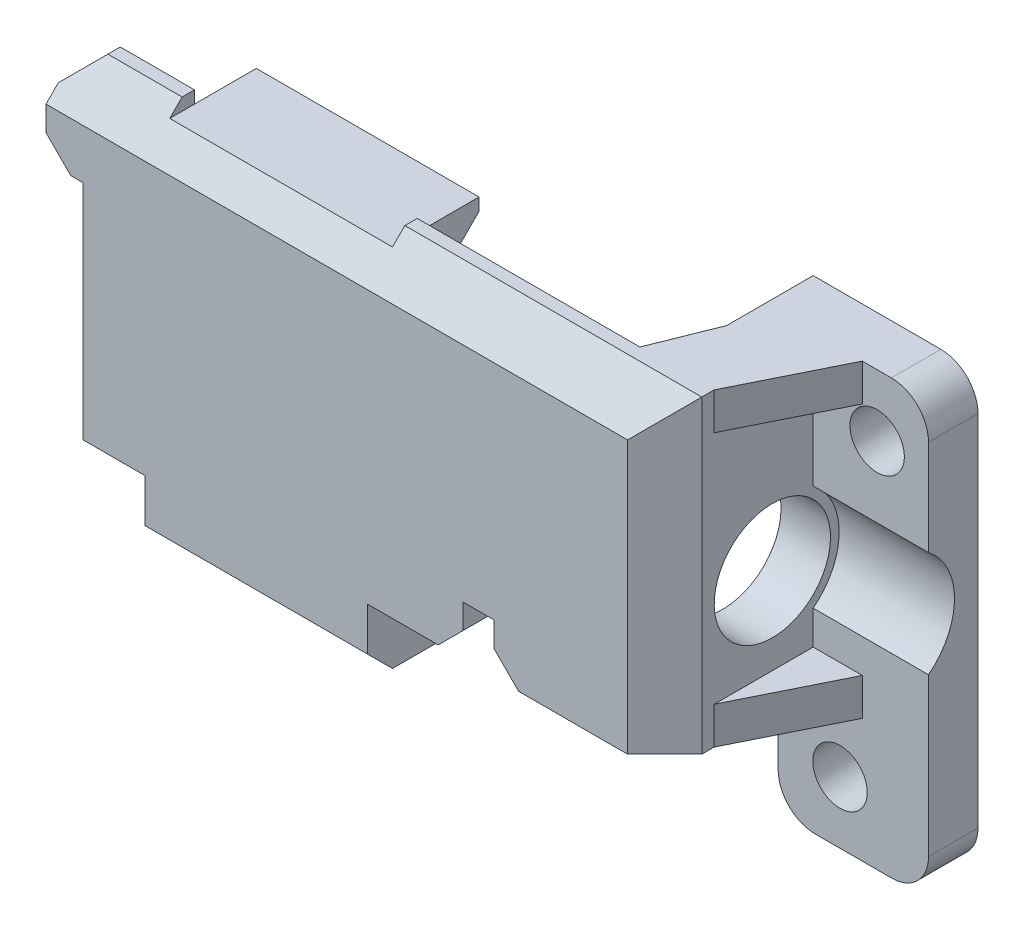
SolidWorks part; units mm, degrees
material "PEI"
ref_plane "前视基准面" through (0, 0, 0) normal (0, 0, 1) x (1, 0, 0)
ref_plane "上视基准面" through (0, 0, 0) normal (0, 1, 0) x (1, 0, 0)
ref_plane "右视基准面" through (0, 0, 0) normal (1, 0, 0) x (0, 0, -1)
other "Configuration Table"
sketch "草图1" plane through (0, 0, 0) normal (0, 0, 1) x (1, 0, 0)
  line L1 (0, 0) -> (9.32, 0)
  line L2 (0, 0) -> (0, 35)
  line L3 (0, 35) -> (9.32, 35)
  line L4 (9.32, 0) -> (9.32, 35)
  line L5 (0, 0) -> (-2.83, 0)
  line L6 (0, 0) -> (0, 10)
  line L7 (0, 10) -> (-2.83, 10)
  line L8 (-2.83, 0) -> (-2.83, 10)
  circle A0 centre (2.17, 5) radius 2.2
  circle A1 centre (5.17, 30) radius 2.2
  dimension "D1" = 4.4
  dimension "D2" = 3
  dimension "D3" = 25
  dimension "D4" = 5
  dimension "D5" = 4.15
  dimension "D6" = 5.17
  dimension "D7" = 5
  dimension "D8" = 5
  dimension "D9" = 10
extrude "凸台-拉伸2" add sketch "草图1" along normal blind 4 contours A0 L2 L1 L4 L3 A1 | A0 L2 L7 L8 L5
sketch "草图2" plane through (0, 0, 0) normal (0, 0, -1) x (-1, 0, 0)
  line L0 (0, 10) -> (2.83, 10) construction
  line L1 (0, 35) -> (4, 35)
  line L2 (0, 35) -> (0, 10)
  line L3 (0, 10) -> (4, 10)
  line L4 (4, 35) -> (4, 10)
  dimension "D2" = 4
extrude "凸台-拉伸3" add sketch "草图2" against normal blind 16
sketch "草图3" plane through (0, 0, 0) normal (1, 0, 0) x (0, 0, -1)
  line L0 (-16, 35) -> (-4, 35) construction
  line L1 (-16, 35) -> (-12, 35)
  line L2 (-16, 35) -> (-16, 10)
  line L3 (-16, 10) -> (-12, 10)
  line L4 (-12, 35) -> (-12, 10)
  line L5 (-16, 35) -> (-16, 10) construction
  line L6 (-16, 10) -> (-4, 10) construction
  dimension "D1" = 4
extrude "凸台-拉伸4" add sketch "草图3" against normal blind 50
sketch "草图4" plane through (0, 0, 12) normal (0, 0, -1) x (-1, 0, 0)
  line L0 (50, 10) -> (4, 10) construction
  line L1 (24, 10) -> (42, 10)
  line L2 (24, 10) -> (24, 3.5)
  line L3 (24, 3.5) -> (42, 3.5)
  line L4 (42, 10) -> (42, 3.5)
  line L5 (4, 35) -> (4, 10) construction
  line L6 (50, 10) -> (50, 35) construction
  dimension "D1" = 20
  dimension "D2" = 8
  dimension "D3" = 6.5
extrude "凸台-拉伸5" add sketch "草图4" against normal up to surface (4 mm away) up to face at (-25, 22.5, 16)
sketch "草图5" plane through (0, 0, 12) normal (0, 0, -1) x (-1, 0, 0)
  line L0 (42, 3.5) -> (42, 10) construction
  line L1 (24, 3.5) -> (42, 3.5)
  line L2 (24, 3.5) -> (24, 7.5)
  line L3 (24, 7.5) -> (42, 7.5)
  line L4 (42, 3.5) -> (42, 7.5)
  line L5 (50, 35) -> (4, 35) construction
  line L6 (24, 35) -> (42, 35)
  line L7 (24, 35) -> (24, 31)
  line L8 (24, 31) -> (42, 31)
  line L9 (42, 35) -> (42, 31)
  dimension "D1" = 4
  dimension "D2" = 18
  dimension "D3" = 4
extrude "凸台-拉伸6" add sketch "草图5" along normal blind 5
sketch "草图6" plane through (0, 0, 12) normal (0, 0, -1) x (-1, 0, 0)
  line L0 (24, 10) -> (4, 10) construction
  line L1 (13.8, 10) -> (16.3, 10)
  line L2 (13.8, 10) -> (13.8, 14)
  line L3 (13.8, 14) -> (16.3, 14)
  line L4 (16.3, 10) -> (16.3, 14)
  line L5 (24, 10) -> (24, 7.5) construction
  line L7 (50, 10) -> (47, 10)
  line L8 (50, 10) -> (50, 28)
  line L9 (50, 28) -> (47, 28)
  line L10 (47, 10) -> (47, 28)
  dimension "D1" = 2.5
  dimension "D2" = 7.7
  dimension "D3" = 4
  dimension "D4" = 3
  dimension "D5" = 18
extrude "切除-拉伸1" cut sketch "草图6" against normal up to surface (4 mm away) up to face at (-29, 14.625, 16)
sketch "草图7" plane through (0, 0, 0) normal (1, 0, 0) x (0, 0, -1)
  line L0 (-12, 35) -> (-12, 10) construction
  line L1 (-16, 10) -> (-4, 10) construction
  circle A0 centre (-7.3, 20) radius 4.7
  dimension "D1" = 9.4
  dimension "D2" = 10
extrude "切除-拉伸2" cut sketch "草图7" against normal through all both and the other way through all
sketch "草图8" plane through (0, 0, 0) normal (1, 0, 0) x (0, 0, -1)
  arc A0 (-4, 23.3466) -> (-4, 16.6534) centre (-7.3, 20) ccw construction
  arc A1 (-4, 23.3466) -> (-4, 16.6534) centre (-7.3, 20) ccw
  circle A2 centre (-7.3, 20) radius 5.4
  arc M1 (-4, 16.6534) -> (-4, 23.3466) centre (-7.3, 20) cw
  line M2 (-4, 23.3466) -> (-4, 35)
  line M6 (-4, 10) -> (-4, 16.6534)
  dimension "D1" = 10.8
extrude "切除-拉伸3" cut sketch "草图8" along normal through all contours A2 M6 M2 M1
sketch "草图9" plane through (0, 10, 0) normal (0, -1, 0) x (1, 0, 0)
  line L0 (3.97, 4) -> (-0.03, 4)
  line L1 (-2.83, 4) -> (9.32, 4) construction
  line L2 (-0.03, 4) -> (0, 12)
  line L3 (0, 16) -> (0, 4) construction
  line L4 (0, 12) -> (3.97, 4)
  line L5 (-6, 12) -> (-4, 12)
  line L6 (-13.8, 12) -> (-4, 12) construction
  line L7 (-4, 12) -> (-4, 7)
  line L8 (-4, 12) -> (-4, 0) construction
  line L9 (-4, 7) -> (-6, 12)
  dimension "D1" = 4
  dimension "D2" = 8
  dimension "D3" = 2
  dimension "D4" = 5
extrude "凸台-拉伸7" add sketch "草图9" against normal blind 3
sketch "草图10" plane through (0, 35, 0) normal (0, 1, 0) x (1, 0, 0)
  line L0 (3.97, -4) -> (0, -4) construction
  line L1 (0, -4) -> (0, -12) construction
  line L2 (0, -12) -> (3.97, -4) construction
  line L3 (-4, -7) -> (-6, -12) construction
  line L4 (-6, -12) -> (-4, -12) construction
  line L5 (-4, -12) -> (-4, -7) construction
  line L6 (3.97, -4) -> (0, -4)
  line L7 (0, -4) -> (0, -12)
  line L8 (0, -12) -> (3.97, -4)
  line L9 (-4, -7) -> (-6, -12)
  line L10 (-6, -12) -> (-4, -12)
  line L11 (-4, -12) -> (-4, -7)
extrude "凸台-拉伸8" add sketch "草图10" against normal blind 3
chamfer "倒角1" distance 3 angle 45 3 edges at (-33, 3.5, 16) (-25, 35, 16) (0, 22.5, 16)
chamfer "倒角2" distance 2 angle 45 7 edges at (-13.8, 10, 14) (-16.3, 10, 14) (-50, 28, 14) (-47, 19, 12) (-50, 35, 12.5) (-33, 7.5, 7) (-33, 31, 7)
fillet "圆角1" radius 3 3 edges at (9.32, 35, 2) (-2.83, 0, 2) (9.32, 0, 2)
sketch "草图11" plane through (0, 0, 7) normal (0, 0, -1) x (-1, 0, 0)
  line L0 (42, 31) -> (42, 35) construction
  line L1 (24, 35) -> (42, 35)
  line L2 (24, 35) -> (24, 34)
  line L3 (24, 34) -> (42, 34)
  line L4 (42, 35) -> (42, 34)
  line L5 (42, 3.5) -> (42, 5.5) construction
  line L6 (24, 3.5) -> (42, 3.5)
  line L7 (24, 3.5) -> (24, 4.5)
  line L8 (24, 4.5) -> (42, 4.5)
  line L9 (42, 3.5) -> (42, 4.5)
  dimension "D1" = 1
  dimension "D2" = 1
extrude "切除-拉伸4" cut sketch "草图11" against normal blind 10
fillet "圆角2" radius 2 2 edges at (-33, 7.5, 12) (-33, 31, 12)
